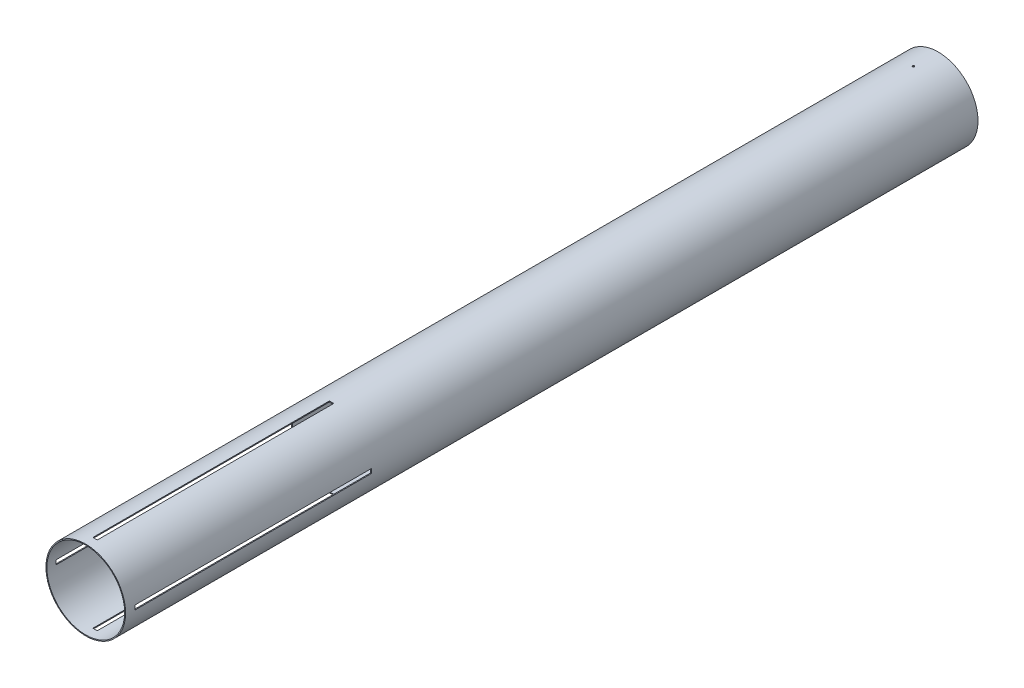
SolidWorks part; units mm, degrees
material "Thornel Mat VMA"
ref_plane "Front Plane" through (0, 0, 0) normal (0, 0, 1) x (1, 0, 0)
ref_plane "Top Plane" through (0, 0, 0) normal (0, 1, 0) x (1, 0, 0)
ref_plane "Right Plane" through (0, 0, 0) normal (1, 0, 0) x (0, 0, -1)
sketch "Sketch1" plane through (0, 0, 0) normal (0, 0, 1) x (1, 0, 0)
  circle A0 centre (0, 0) radius 62.5
  circle A1 centre (0, 0) radius 64
  dimension "D1" = 125
  dimension "D2" = 128
extrude "Boss-Extrude1" add sketch "Sketch1" along normal mid plane 1370
sketch "Sketch2" plane through (0, 0, 0) normal (0, 1, 0) x (1, 0, 0)
  line L0 (3.5, -670) -> (3.5, -290)
  line L2 (3.5, -290) -> (-3.5, -290)
  line L3 (-3.5, -290) -> (-3.5, -670)
  line L4 (-3.5, -670) -> (3.5, -670)
  line L6 (0, -685) -> (0, -84.8795) construction
  line L7 (-64, -685) -> (64, -685) construction
  dimension "D1" = 380
  dimension "D2" = 7
  dimension "D3" = 15
extrude "Cut-Extrude1" cut sketch "Sketch2" against normal mid plane 150
pattern_circular "CirPattern1" count 4 over 360 about axis through (0, 0, 685) along (0, 0, 1) of "Cut-Extrude1"
sketch "Sketch3" plane through (0, 0, 0) normal (0, 1, 0) x (1, 0, 0)
  line L0 (64, 685) -> (-64, 685) construction
  circle A0 centre (0, 645) radius 1.5
  dimension "D1" = 40
  dimension "D2" = 3
extrude "Cut-Extrude2" cut sketch "Sketch3" along normal through all
